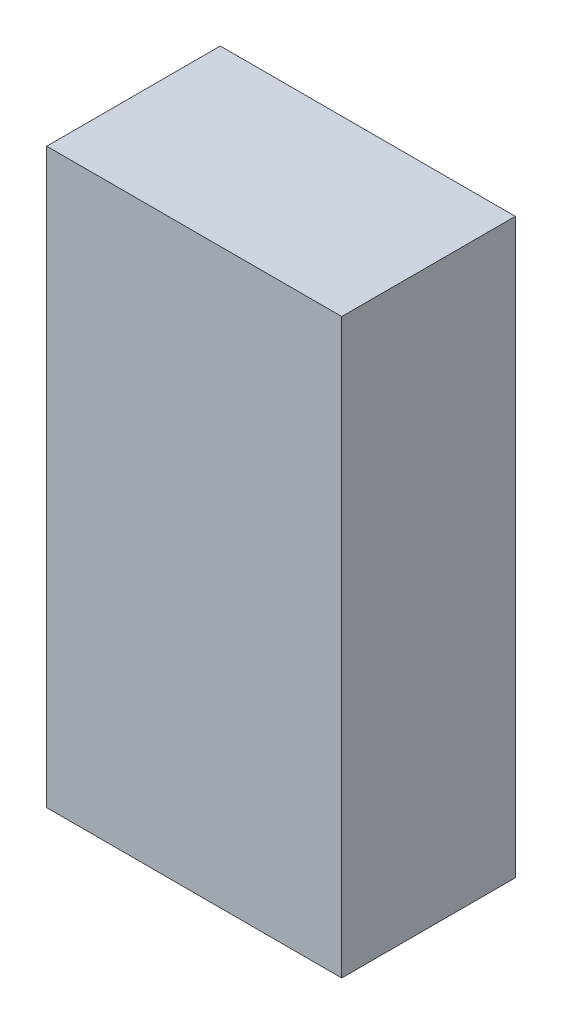
SolidWorks part; units mm, degrees
ref_plane "Ebene vorne" through (0, 0, 0) normal (0, 0, 1) x (1, 0, 0)
ref_plane "Ebene oben" through (0, 0, 0) normal (0, 1, 0) x (1, 0, 0)
ref_plane "Ebene rechts" through (0, 0, 0) normal (1, 0, 0) x (0, 0, -1)
sketch "Skizze1" plane through (0, 0, 0) normal (0, 0, 1) x (1, 0, 0)
  line L0 (-0.85, 1.6508) -> (0.85, 1.6508)
  line L1 (0.85, 1.6508) -> (0.85, -1.65)
  line L2 (0.85, -1.65) -> (-0.85, -1.65)
  line L3 (-0.85, -1.65) -> (-0.85, 1.6508)
extrude "Component_Outline" add sketch "Skizze1" along normal blind 1 separate body
sketch3d "3D-Skizze1"
  line L0 (0, 0, 0) -> (1, 0, 0)
  line L1 (0, 0, 0) -> (0, 1, 0)
  line L2 (0, 0, 0) -> (0, 0, 1)
  point P0 (0, 0, 0)
